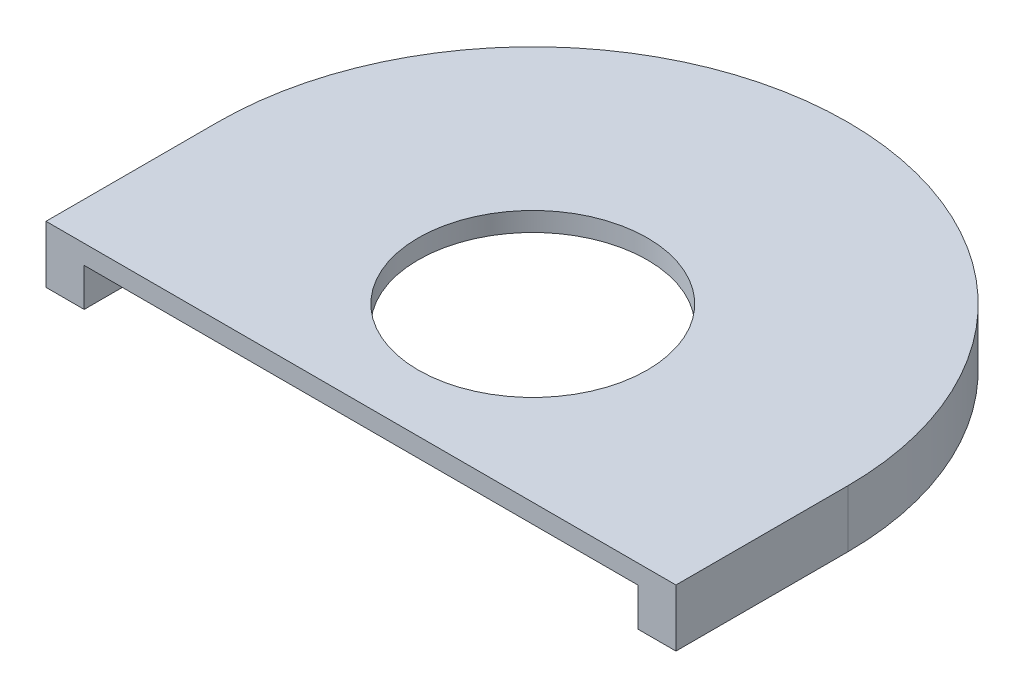
SolidWorks part; units mm, degrees
ref_plane "Front Plane" through (0, 0, 0) normal (0, 0, 1) x (1, 0, 0)
ref_plane "Top Plane" through (0, 0, 0) normal (0, 1, 0) x (1, 0, 0)
ref_plane "Right Plane" through (0, 0, 0) normal (1, 0, 0) x (0, 0, -1)
sketch "Sketch1" plane through (0, 0, 0) normal (0, 1, 0) x (1, 0, 0)
  line L1 (-14.5, 14.5) -> (14.5, 14.5)
  line L2 (-14.5, 14.5) -> (-14.5, -14.5)
  line L3 (-14.5, -14.5) -> (14.5, -14.5)
  line L4 (14.5, 14.5) -> (14.5, -14.5)
  circle A0 centre (0, 0) radius 14.5
  circle A1 centre (0, 0) radius 6
  dimension "D1" = 12
  dimension "D2" = 29
extrude "Boss-Extrude1" add sketch "Sketch1" along normal blind 1 contours A0 A1 | A0 L2 L3 | A0 L3 L4
sketch "Sketch2" plane through (0, 1, 0) normal (0, 1, 0) x (1, 0, 0)
  line L0 (-16.5, 0) -> (-14.5, 0)
  line L1 (-16.5, 16.5) -> (16.5, 16.5)
  line L2 (-16.5, 16.5) -> (-16.5, -16.5)
  line L3 (-16.5, -16.5) -> (16.5, -16.5)
  line L4 (16.5, 16.5) -> (16.5, -16.5)
  line L5 (14.5, 0) -> (16.5, 0)
  circle A0 centre (0, 0) radius 16.5
  arc M7 (14.5, 0) -> (-14.5, 0) centre (0, 0) ccw
  line M8 (-14.5, 0) -> (-14.5, -14.5)
  line M9 (-14.5, -14.5) -> (14.5, -14.5)
  line M10 (14.5, -14.5) -> (14.5, 0)
  dimension "D1" = 33
extrude "Boss-Extrude2" add sketch "Sketch2" against normal blind 3 contours A0 L3 L4 M10 M9 | A0 M9 | A0 L2 L3 M9 M8 | L0 A0 M8 | A0 L5 M10 | L5 A0 L0 M7
sketch "Sketch3" plane through (0, -2, 0) normal (0, -1, 0) x (1, 0, 0)
  line L0 (16.5, 0) -> (16.5, 16.5) construction
  line L1 (-16.5, 16.5) -> (16.5, 16.5)
  line L2 (-16.5, 16.5) -> (-16.5, 9)
  line L3 (-16.5, 9) -> (16.5, 9)
  line L4 (16.5, 16.5) -> (16.5, 9)
  line M5 (-14.5, 0) -> (-14.5, 14.5)
  line M6 (-14.5, 14.5) -> (14.5, 14.5)
  line M7 (14.5, 14.5) -> (14.5, 0)
  line M9 (16.5, 0) -> (16.5, 16.5)
  line M10 (16.5, 16.5) -> (-16.5, 16.5)
  line M11 (-16.5, 16.5) -> (-16.5, 0)
  dimension "D1" = 7.5
extrude "Cut-Extrude1" cut sketch "Sketch3" against normal through all both and the other way through all contours L3 M11 M5 M6 M7 M9 M10 | L3 M5 M7 M6
